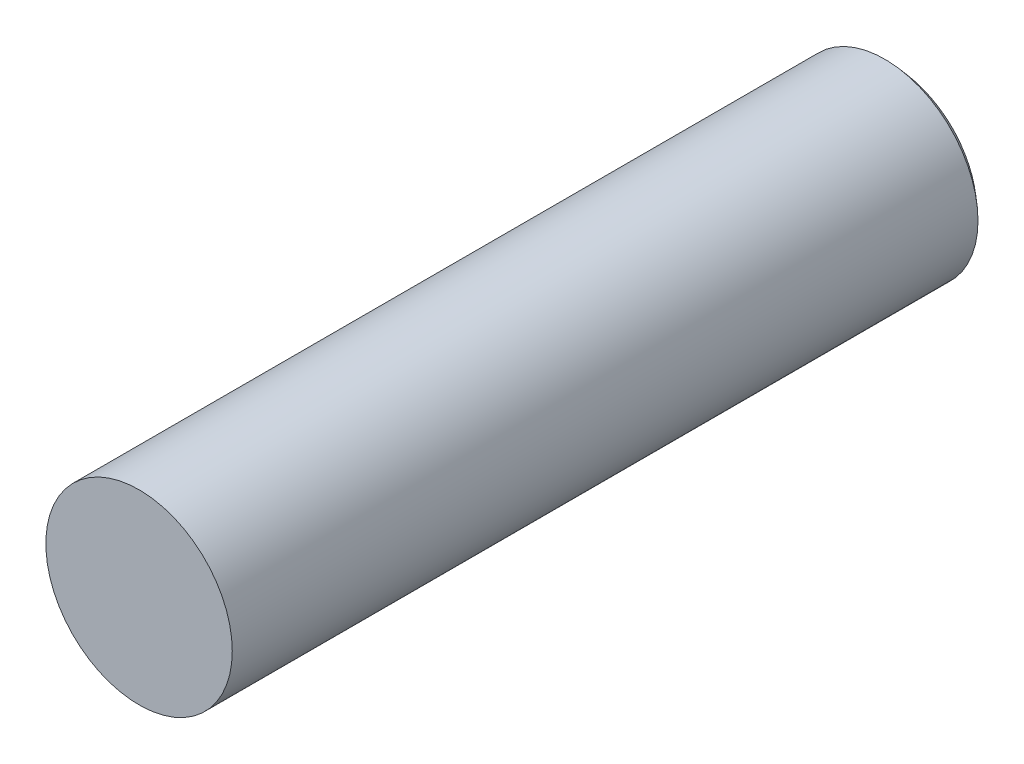
SolidWorks part; units mm, degrees
material "6061 Alloy"
ref_plane "Front" through (0, 0, 0) normal (0, 0, 1) x (1, 0, 0)
ref_plane "Top" through (0, 0, 0) normal (0, 1, 0) x (1, 0, 0)
ref_plane "Right" through (0, 0, 0) normal (1, 0, 0) x (0, 0, -1)
sketch "Sketch2" plane through (0, 0, 0) normal (0, 0, 1) x (1, 0, 0)
  circle A0 centre (0, 0) radius 250
  dimension "D1" = 500
extrude "Boss-Extrude1" add sketch "Sketch2" along normal blind 2000
sketch "Sketch7" plane through (0, 0, 0) normal (0, 1, 0) x (1, 0, 0)
  line L0 (0, 0) -> (0, 100)
  line L1 (0, 0) -> (250, 0)
  arc A0 (0, 100) -> (250, 0) centre (0, -262.5) cw
  dimension "D1" = 100
revolve "Revolve1" add sketch "Sketch7" angle 360 about L0
